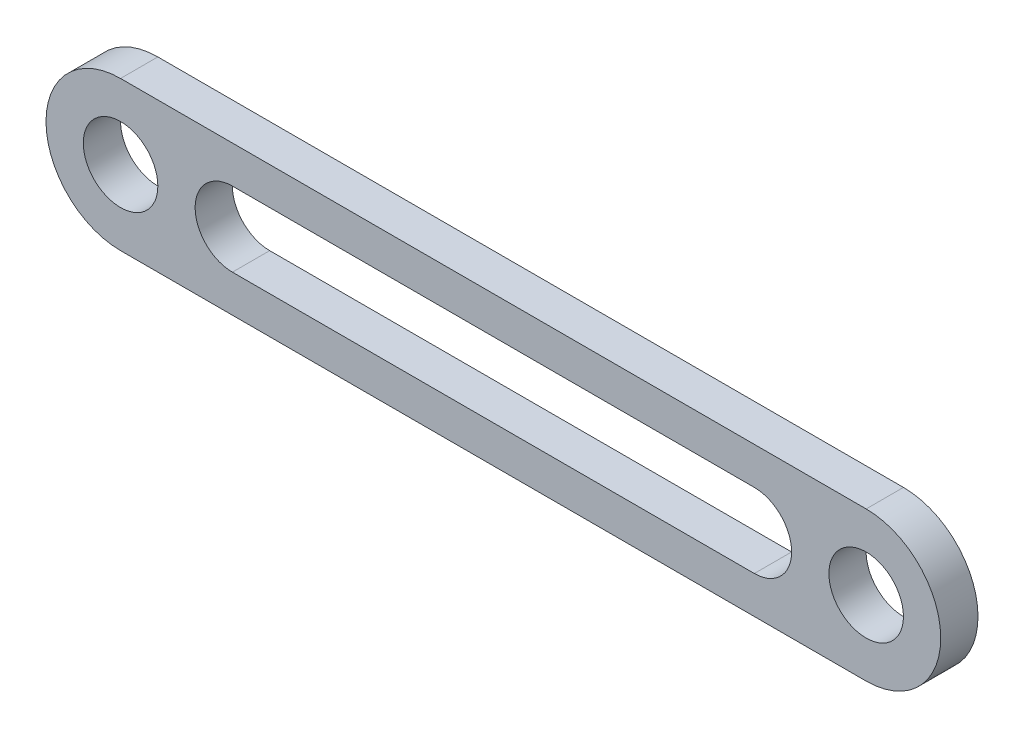
SolidWorks part; units mm, degrees
ref_plane "Plano frontal" through (0, 0, 0) normal (0, 0, 1) x (1, 0, 0)
ref_plane "Plano superior" through (0, 0, 0) normal (0, 1, 0) x (1, 0, 0)
ref_plane "Plano direito" through (0, 0, 0) normal (1, 0, 0) x (0, 0, -1)
sketch "Esboço1" plane through (0, 0, 0) normal (0, 0, 1) x (1, 0, 0)
  line L9 (-119.4469, 13.2441) -> (-19.2955, 13.2441)
  line L11 (-119.4469, -6.7559) -> (-19.2955, -6.7559)
  line L12 (-19.2955, 13.2441) -> (-19.2955, 13.243)
  line L13 (-19.2955, -6.7547) -> (-19.2955, -6.7559)
  line L15 (-104.4469, 8.2441) -> (-34.4469, 8.2441)
  line L17 (-104.4469, -1.7559) -> (-34.4469, -1.7559)
  circle A0 centre (-119.4469, 3.2441) radius 5
  circle A1 centre (-19.4469, 3.2441) radius 5
  arc A2 (-119.4469, 13.2441) -> (-119.4469, -6.7559) centre (-119.4469, 3.2441) ccw
  arc A3 (-19.2955, -6.7547) -> (-19.4469, 13.2441) centre (-19.4469, 3.2441) ccw
  arc A4 (-104.4469, 8.2441) -> (-104.4469, -1.7559) centre (-104.4469, 3.2441) ccw
  arc A6 (-34.4469, -1.7559) -> (-34.4469, 8.2441) centre (-34.4469, 3.2441) ccw
  dimension "D1" = 10
  dimension "D2" = 10
  dimension "D4" = 20
  dimension "D7" = 10
  dimension "D8" = 10
  dimension "D9" = 10
  dimension "D3" = 100
  dimension "D5" = 15
  dimension "D6" = 15
extrude "Ressalto-extrusão1" add sketch "Esboço1" along normal blind 5 contours A3 L9 A2 L11 L13 A6 L17 A4 L15 A0 A1
